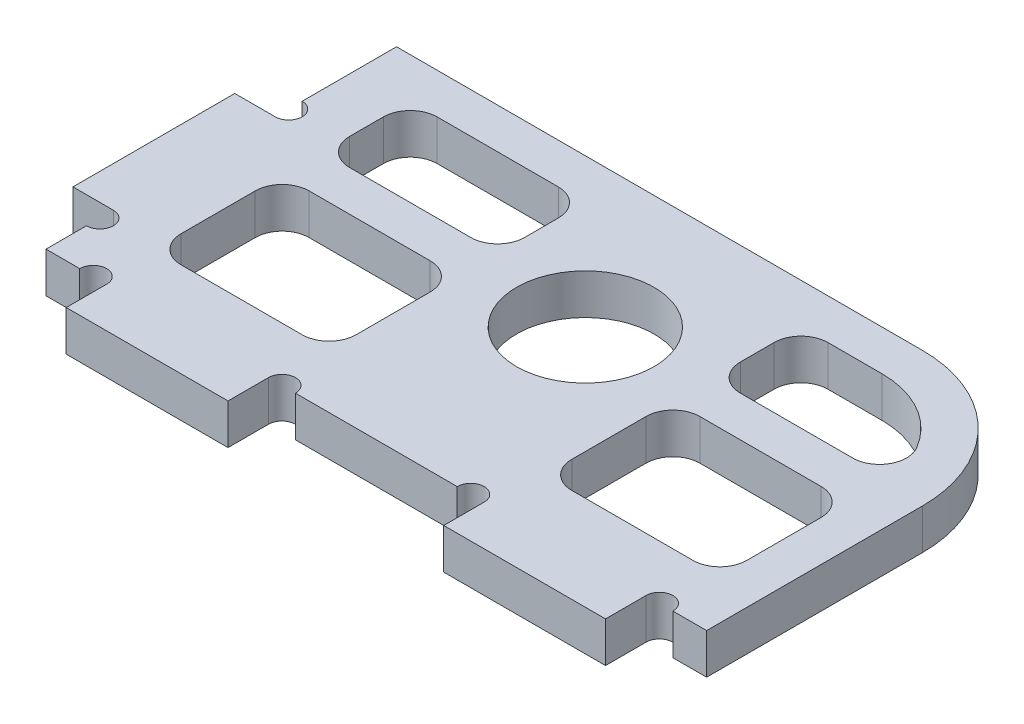
SolidWorks part; units mm, degrees
material "碳纤维"
ref_plane "前视基准面" through (0, 0, 0) normal (0, 0, 1) x (1, 0, 0)
ref_plane "上视基准面" through (0, 0, 0) normal (0, 1, 0) x (1, 0, 0)
ref_plane "右视基准面" through (0, 0, 0) normal (1, 0, 0) x (0, 0, -1)
sketch "草图1" plane through (0, 0, 0) normal (0, 1, 0) x (1, 0, 0)
  line L1 (-24.5, -13) -> (24.5, -13)
  line L2 (-24.5, -13) -> (-24.5, 13)
  line L3 (-24.5, 13) -> (24.5, 13)
  line L4 (24.5, -13) -> (24.5, 13)
  line L5 (0, 13) -> (0, -13) construction
  line L6 (-24.5, 0) -> (24.5, 0) construction
  circle A0 centre (0.5, 2) radius 5.1
  point P0 (0, 0)
  dimension "D1" = 24
  dimension "D5" = 10.2
  dimension "D2" = 49
  dimension "D3" = 26
  dimension "D4" = 15
extrude "凸台-拉伸1" add sketch "草图1" along normal blind 3
sketch "草图2" plane through (0, 3, 0) normal (0, 1, 0) x (1, 0, 0)
  line L5 (-24.5, 13) -> (-24.5, -13) construction
  line L8 (-24.5, -13) -> (24.5, -13) construction
  line L9 (-20, -13) -> (-8, -13)
  line L10 (-20, -13) -> (-20, -16)
  line L11 (-20, -16) -> (-8, -16)
  line L12 (-8, -13) -> (-8, -16)
  line L13 (-14, -16) -> (-14, -13) construction
  line L14 (-20, -14.5) -> (-8, -14.5) construction
  line L15 (0, 0) -> (0, -13) construction
  line L20 (20, -16) -> (8, -16)
  line L21 (8, -13) -> (8, -16)
  line L22 (-24.5, 0) -> (24.5, 0) construction
  line L23 (24.5, -13) -> (24.5, 13) construction
  line L24 (20, -13) -> (8, -13)
  line L25 (20, -13) -> (20, -16)
  point P64 (-14, -14.5)
  dimension "D4" = 28
  dimension "D5" = 12
  dimension "D6" = 3
sketch "草图5" plane through (0, 0, 0) normal (0, -1, 0) x (1, 0, 0)
  line L0 (-24.5, -13) -> (-24.5, 13) construction
  line L1 (-24.5, 8) -> (-27.5, 8)
  line L2 (-24.5, 8) -> (-24.5, -4)
  line L3 (-24.5, -4) -> (-27.5, -4)
  line L4 (-27.5, 8) -> (-27.5, -4)
  line L5 (-26, -4) -> (-26, 8) construction
  line L6 (-24.5, 2) -> (-27.5, 2) construction
  line L7 (24.5, -13) -> (-24.5, -13) construction
  point P108 (-26, 2)
  dimension "D1" = 12
  dimension "D2" = 3
  dimension "D3" = 15
extrude "凸台-拉伸2" add sketch "草图5" against normal up to surface (3 mm away) up to face at (0, 3, 0)
extrude "凸台-拉伸3" add sketch "草图2" against normal up to surface (3 mm away) up to face at (-13, 0, 1)
sketch "草图8" plane through (0, 3, 0) normal (0, 1, 0) x (1, 0, 0)
  line L0 (20, -13) -> (24.5, -13) construction
  line L1 (14, -16) -> (14, 13) construction
  line L2 (8, -16) -> (20, -16) construction
  line L3 (24.5, 13) -> (-24.5, 13) construction
  line L4 (0, -13) -> (0, 0) construction
  line L5 (-8, -13) -> (8, -13) construction
  line L6 (-24.5, -8) -> (-24.5, -13) construction
  line L7 (-27.5, -2) -> (-17.6174, -2) construction
  line L8 (-27.5, 4) -> (-27.5, -8) construction
  circle A0 centre (21, -13) radius 1
  circle A1 centre (7, -13) radius 1
  circle A2 centre (-7, -13) radius 1
  circle A3 centre (-21, -13) radius 1
  circle A4 centre (-24.5, -9) radius 1
  circle A5 centre (-24.5, 5) radius 1
  dimension "D1" = 2
extrude "切除-拉伸5" cut sketch "草图8" against normal through all
fillet "圆角1" radius 10 1 edges at (24.5, 1.5, -13)
sketch "草图6" plane through (0, 3, 0) normal (0, 1, 0) x (1, 0, 0)
  line L0 (0.5, 2) -> (24.5, 2) construction
  line L5 (24.5, -13) -> (24.5, 3) construction
  line L23 (14.5, 13) -> (-24.5, 13) construction
  line L25 (0.5, 2) -> (0.5, 7.1) construction
  line L26 (-20.4821, 0.5) -> (-7.5, 0.5)
  line L36 (-20.4821, 0.5) -> (-20.4821, -9)
  line L44 (-20.4821, -9) -> (-7.5, -9)
  line L45 (-7.5, 0.5) -> (-7.5, -9)
  line L46 (-13.9911, -9) -> (-13.9911, 0.5) construction
  line L47 (-20.4821, -4.25) -> (-7.5, -4.25) construction
  line L48 (-20.4821, 3.5) -> (-7.5, 3.5)
  line L49 (-20.4821, 3.5) -> (-20.4821, 10)
  line L50 (-20.4821, 10) -> (-7.5, 10)
  line L51 (-7.5, 3.5) -> (-7.5, 10)
  line L52 (-13.9911, 10) -> (-13.9911, 3.5) construction
  line L53 (-20.4821, 6.75) -> (-7.5, 6.75) construction
  line L54 (21.4821, -9) -> (8.5, -9)
  line L55 (8.5, 0.5) -> (8.5, -9)
  line L56 (21.4821, 0.5) -> (8.5, 0.5)
  line L57 (21.4821, 0.5) -> (21.4821, -9)
  line L59 (8.5, 3.5) -> (8.5, 10)
  line L60 (21.4821, 3.5) -> (8.5, 3.5)
  line L61 (8.5, 10) -> (14.5, 10)
  line L62 (-24.5, -13) -> (-22, -13) construction
  circle A0 centre (0.5, 2) radius 5.1 construction
  arc A1 (21.4821, 3.5) -> (14.5, 10) centre (14.5, 3) ccw
  arc A2 (24.5, 3) -> (14.5, 13) centre (14.5, 3) ccw construction
  point P100 (-13.9911, -4.25)
  point P138 (-13.9911, 6.75)
  dimension "D4" = 3
  dimension "D2" = 3
  dimension "D3" = 3
  dimension "D5" = 16
  dimension "D1" = 4
extrude "切除-拉伸3" cut sketch "草图6" against normal through all
fillet "圆角2" radius 2 15 edges at (-20.4821, 1.5, -0.5) (-7.5, 1.5, 9) (-20.4821, 1.5, 9) (21.4821, 1.5, -3.5) (8.5, 1.5, -3.5) (8.5, 1.5, -10) (21.4821, 1.5, 9) (8.5, 1.5, 9) (8.5, 1.5, -0.5) (21.4821, 1.5, -0.5) (-20.4821, 1.5, -10) (-7.5, 1.5, -10) (-7.5, 1.5, -3.5) (-20.4821, 1.5, -3.5) (-7.5, 1.5, -0.5)
move or copy body "实体-移动/复制1" [suppressed] bodies to move or copy 110
